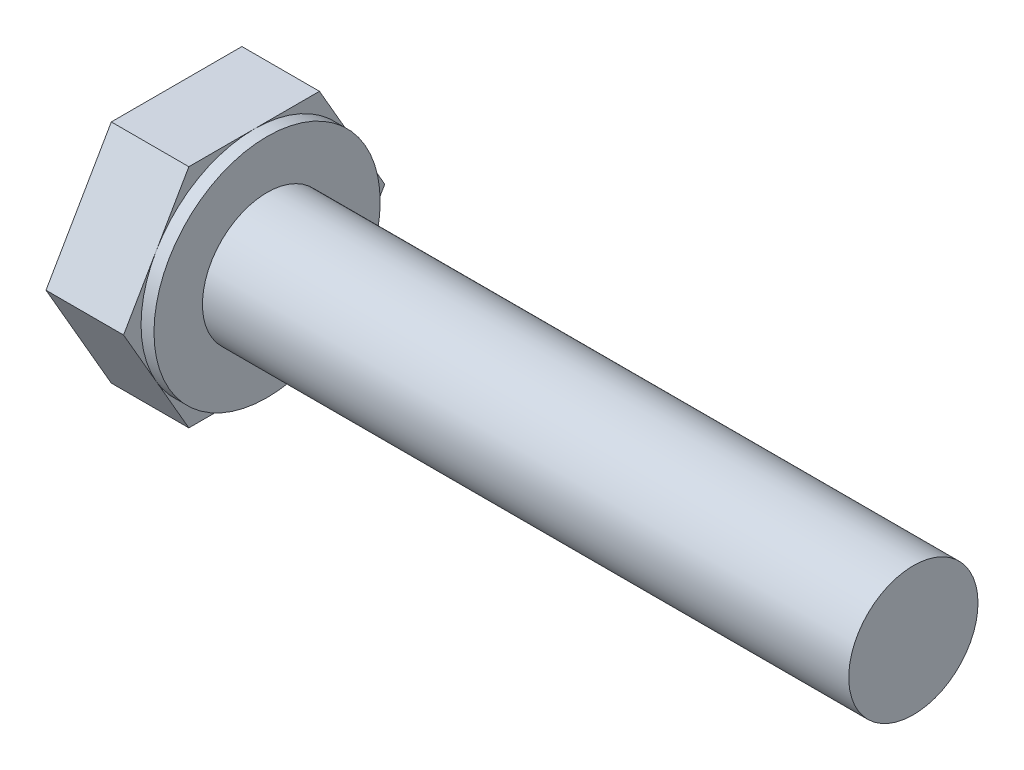
SolidWorks part; units mm, degrees
material "Plain Carbon Steel"
ref_plane "Front Plane" through (0, 0, 0) normal (0, 0, 1) x (1, 0, 0)
ref_plane "Top Plane" through (0, 0, 0) normal (0, 1, 0) x (1, 0, 0)
ref_plane "Right Plane" through (0, 0, 0) normal (1, 0, 0) x (0, 0, -1)
sketch "Sketch1" plane through (0, 0, 0) normal (1, 0, 0) x (0, 0, -1)
  line L1 (-4.0415, 0) -> (-2.0207, -3.5)
  line L2 (-2.0207, -3.5) -> (2.0207, -3.5)
  line L3 (2.0207, -3.5) -> (4.0415, 0)
  line L4 (4.0415, 0) -> (2.0207, 3.5)
  line L5 (2.0207, 3.5) -> (-2.0207, 3.5)
  line L6 (-2.0207, 3.5) -> (-4.0415, 0)
  circle A0 centre (0, 0) radius 3.5 construction
  dimension "D1" = 7
extrude "Boss-Extrude1" add sketch "Sketch1" against normal blind 2.4
sketch "Sketch2" plane through (0, 0, 0) normal (1, 0, 0) x (0, 0, -1)
  line L0 (2.0207, 3.5) -> (-2.0207, 3.5) construction
  circle A0 centre (0, 0) radius 3.5
extrude "Boss-Extrude2" add sketch "Sketch2" along normal blind 0.4
sketch "Sketch3" plane through (0.4, 0, 0) normal (1, 0, 0) x (0, 0, -1)
  circle A0 centre (0, 0) radius 2
  dimension "D1" = 4
extrude "Boss-Extrude3" add sketch "Sketch3" along normal blind 20
